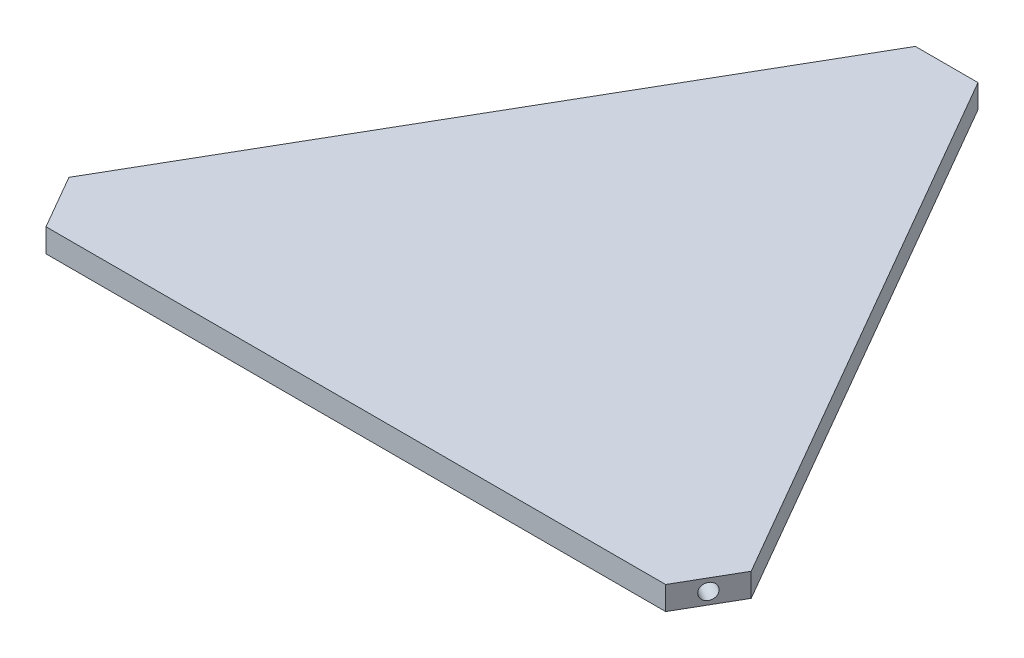
SolidWorks part; units mm, degrees
ref_plane "Front Plane" through (0, 0, 0) normal (0, 0, 1) x (1, 0, 0)
ref_plane "Top Plane" through (0, 0, 0) normal (0, 1, 0) x (1, 0, 0)
ref_plane "Right Plane" through (0, 0, 0) normal (1, 0, 0) x (0, 0, -1)
sketch "Sketch1" plane through (0, 0, 0) normal (0, 1, 0) x (1, 0, 0)
  line L0 (-12.7, 152.4) -> (-138.3323, -65.2015)
  line L1 (-125.6323, -87.1985) -> (125.6323, -87.1985)
  line L2 (138.3323, -65.2015) -> (12.7, 152.4)
  line L3 (0, 0) -> (131.9823, -76.2) construction
  line L4 (0, 0) -> (-131.9823, -76.2) construction
  line L5 (0, 0) -> (0, 152.4) construction
  line L6 (12.7, 152.4) -> (-12.7, 152.4)
  line L7 (-138.3323, -65.2015) -> (-125.6323, -87.1985)
  line L8 (138.3323, -65.2015) -> (125.6323, -87.1985)
  dimension "D1" = 152.4
  dimension "D2" = 25.4
  dimension "D3" = 120
extrude "Boss-Extrude1" add sketch "Sketch1" along normal mid plane 9.525
hole_wizard "1/4 (0.25) Diameter Hole1" positions "Sketch2" profile "Sketch4" hole size "1/4" standard "ANSI Inch"
sketch "Sketch2" plane through (131.9823, 0, 76.2) normal (0.866, 0, 0.5) x (0.5, 0, -0.866)
  point P0 (0, 0)
sketch "Sketch4" plane through (131.9823, 0, 76.2) normal (0, 1, 0) x (0.5, 0, -0.866)
  line L0 (0, 0) -> (0, 14.6077)
  line L1 (0, 14.6077) -> (3.175, 12.7)
  line L2 (3.175, 12.7) -> (3.175, 0)
  line L5 (3.175, 0) -> (0, 0)
  line L10 (0, 14.6077) -> (-3.175, 12.7) construction
  line L11 (0, -6.35) -> (0, 107.95) construction
  dimension "Hole Dia." = 6.35
  dimension "Hole Depth" = 12.7
  dimension "Drill Angle" = 118
pattern_circular "CirPattern1" count 3 over 360 about axis through (0, 4.7625, 0) along (0, 1, 0) of "1/4 (0.25) Diameter Hole1"
